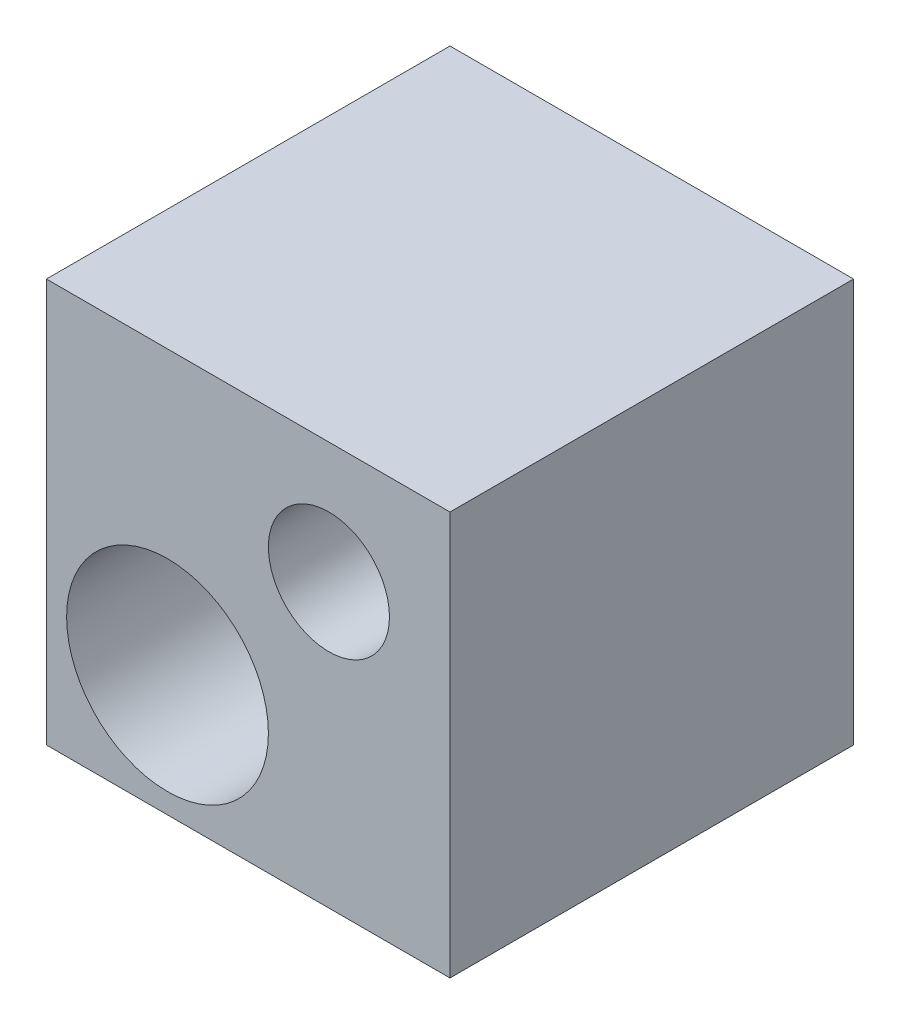
SolidWorks part; units mm, degrees
ref_plane "Front Plane" through (0, 0, 0) normal (0, 0, 1) x (1, 0, 0)
ref_plane "Top Plane" through (0, 0, 0) normal (0, 1, 0) x (1, 0, 0)
ref_plane "Right Plane" through (0, 0, 0) normal (1, 0, 0) x (0, 0, -1)
sketch "Sketch1" plane through (0, 0, 0) normal (0, 0, 1) x (1, 0, 0)
  line L1 (0, 0) -> (10, 0)
  line L2 (0, 0) -> (0, 10)
  line L3 (0, 10) -> (10, 10)
  line L4 (10, 0) -> (10, 10)
extrude "Boss-Extrude1" add sketch "Sketch1" along normal blind 10
sketch "Sketch2" plane through (0, 0, 10) normal (0, 0, 1) x (1, 0, 0)
  circle A0 centre (3, 3) radius 2.5
extrude "Cut-Extrude1" cut sketch "Sketch2" against normal through all
sketch "Sketch3" plane through (0, 0, 10) normal (0, 0, 1) x (1, 0, 0)
  circle A0 centre (7, 7) radius 1.5
extrude "Cut-Extrude2" cut sketch "Sketch3" against normal through all
